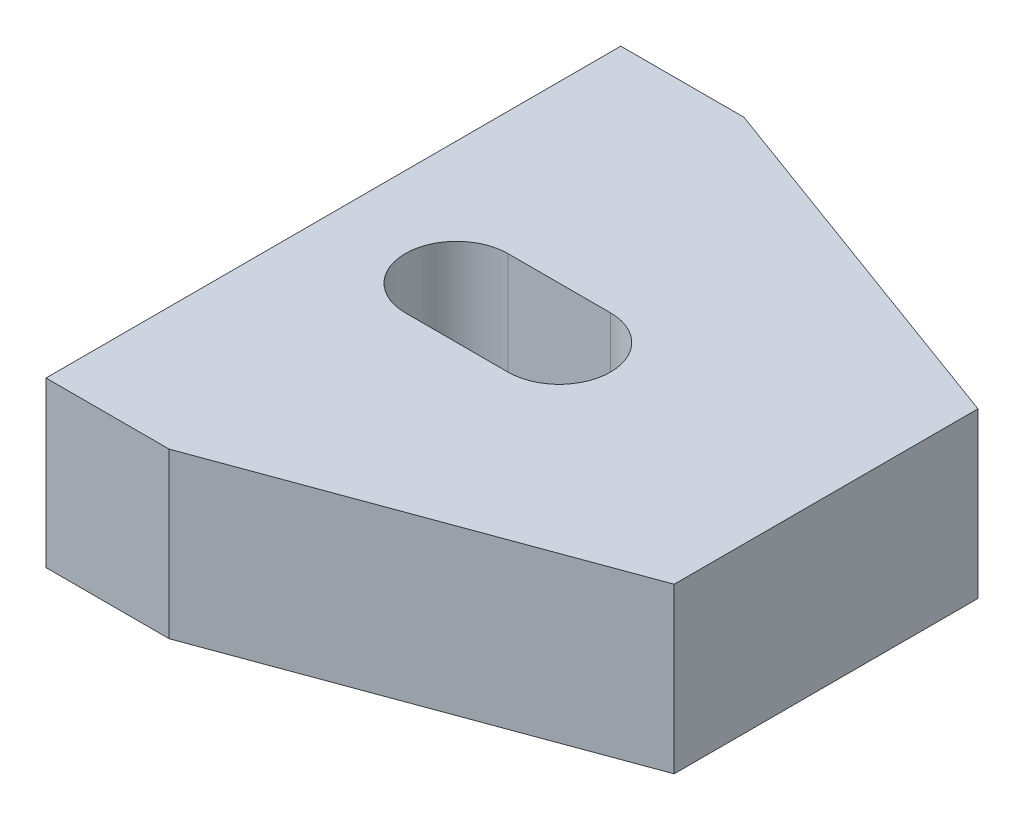
SolidWorks part; units mm, degrees
material "ABS"
ref_plane "Front Plane" through (0, 0, 0) normal (0, 0, 1) x (1, 0, 0)
ref_plane "Top Plane" through (0, 0, 0) normal (0, 1, 0) x (1, 0, 0)
ref_plane "Right Plane" through (0, 0, 0) normal (1, 0, 0) x (0, 0, -1)
sketch "Sketch1" plane through (0, 0, 0) normal (0, 1, 0) x (1, 0, 0)
  line L0 (-15.24, 8.89) -> (-15.24, -8.89)
  line L1 (-15.24, -8.89) -> (-11.43, -8.89)
  line L2 (-11.43, -8.89) -> (0, -4.699)
  line L3 (0, -4.699) -> (0, 4.699)
  line L4 (0, 4.699) -> (-11.43, 8.89)
  line L5 (-11.43, 8.89) -> (-15.24, 8.89)
  line L6 (3.81, -1000.8756) -> (3.81, 48999.1244) construction
  line L7 (-11.43, 0) -> (-8.255, 0) construction
  line L8 (-11.43, 1.5875) -> (-8.255, 1.5875)
  line L9 (-11.43, -1.5875) -> (-8.255, -1.5875)
  arc A0 (-11.43, 1.5875) -> (-11.43, -1.5875) centre (-11.43, 0) ccw
  arc A1 (-8.255, -1.5875) -> (-8.255, 1.5875) centre (-8.255, 0) ccw
  point P11 (-9.8425, 0)
  point P16 (0, 0)
  point P17 (-10.7489, -8.89)
  dimension "D3" = 1.5875
  dimension "D1" = 15.24
  dimension "D2" = 3.81
  dimension "D4" = 3.175
  dimension "D5" = 3.81
  dimension "D6" = 9.398
  dimension "D7" = 17.78
  dimension "D8" = 3.81
extrude "Boss-Extrude1" add sketch "Sketch1" along normal blind 5.08
